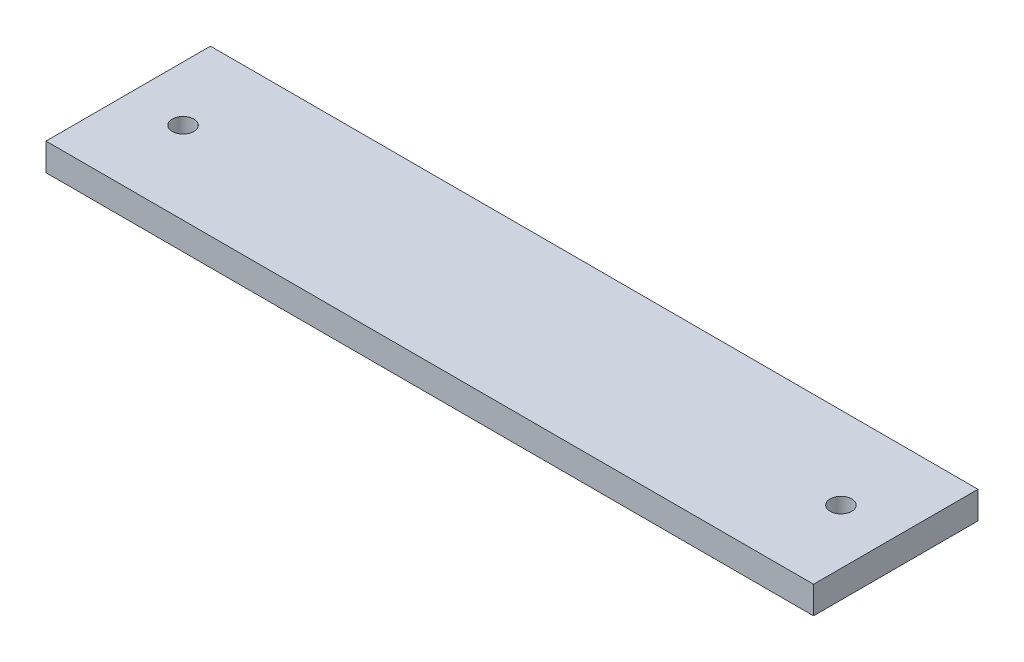
SolidWorks part; units mm, degrees
ref_plane "Front Plane" through (0, 0, 0) normal (0, 0, 1) x (1, 0, 0)
ref_plane "Top Plane" through (0, 0, 0) normal (0, 1, 0) x (1, 0, 0)
ref_plane "Right Plane" through (0, 0, 0) normal (1, 0, 0) x (0, 0, -1)
sketch "Sketch1" plane through (0, 0, 0) normal (0, 1, 0) x (1, 0, 0)
  line L0 (0, 19.05) -> (12.7, 19.05)
  line L1 (0, 0) -> (177.8, 0)
  line L2 (0, 0) -> (0, 38.1)
  line L3 (0, 38.1) -> (177.8, 38.1)
  line L4 (177.8, 0) -> (177.8, 38.1)
  line L5 (177.8, 19.05) -> (165.1, 19.05)
  circle A0 centre (12.7, 19.05) radius 2.5
  circle A1 centre (12.7, 19.05) radius 7 construction
  circle A2 centre (165.1, 19.05) radius 2.5
  circle A3 centre (165.1, 19.05) radius 7 construction
  dimension "D4" = 5
  dimension "D5" = 14
  dimension "D7" = 5
  dimension "D8" = 14
  dimension "D1" = 177.8
  dimension "D2" = 38.1
  dimension "D3" = 12.7
  dimension "D6" = 12.7
extrude "Boss-Extrude1" add sketch "Sketch1" along normal blind 6.35
